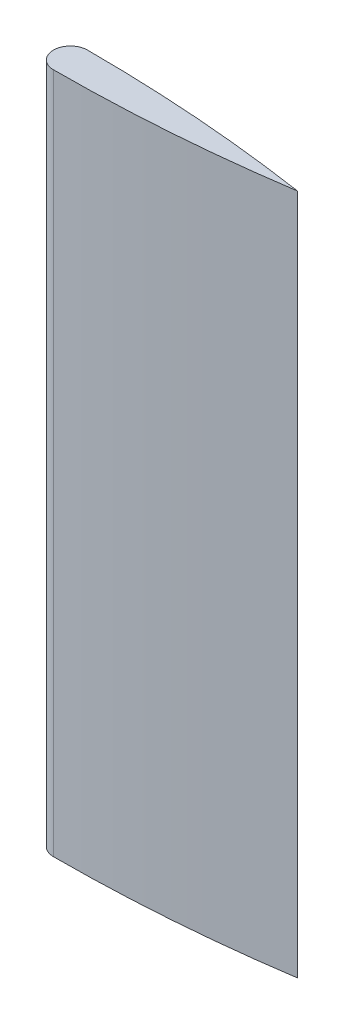
SolidWorks part; units mm, degrees
material "AISI 304"
ref_plane "Plan de face" through (0, 0, 0) normal (0, 0, 1) x (1, 0, 0)
ref_plane "Plan de dessus" through (0, 0, 0) normal (0, 1, 0) x (1, 0, 0)
ref_plane "Plan de droite" through (0, 0, 0) normal (1, 0, 0) x (0, 0, -1)
sketch "Sketch1" plane through (0, 0, 0) normal (0, 1, 0) x (1, 0, 0)
  arc A0 (0, 4.5) -> (0, -4.5) centre (0, 0) ccw
  arc A1 (0, 4.5) -> (60, 0) centre (0, -397.75) cw
  arc A2 (60, 0) -> (0, -4.5) centre (0, 397.75) cw
  point P8 (152.4, 0)
  dimension "D2" = 9
  dimension "D1" = 60
extrude "Boss-Extrude1" add sketch "Sketch1" along normal blind 180
